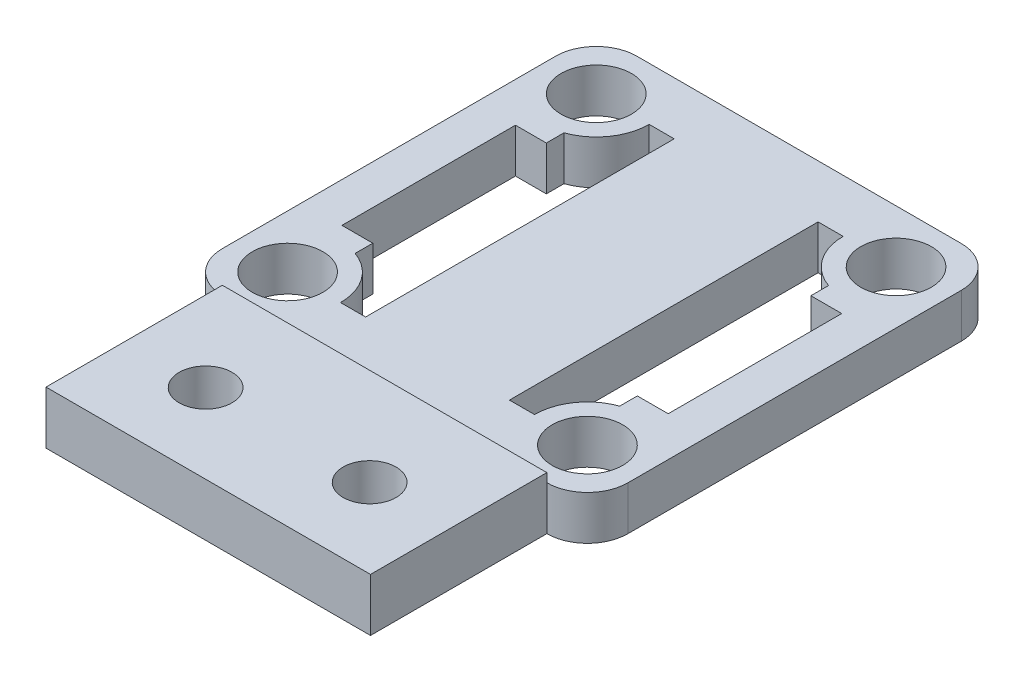
SolidWorks part; units mm, degrees
ref_plane "Front Plane" through (0, 0, 0) normal (0, 0, 1) x (1, 0, 0)
ref_plane "Top Plane" through (0, 0, 0) normal (0, 1, 0) x (1, 0, 0)
ref_plane "Right Plane" through (0, 0, 0) normal (1, 0, 0) x (0, 0, -1)
sketch "Sketch1" plane through (0, 0, 0) normal (0, 1, 0) x (1, 0, 0)
  line L1 (-12.6491, 14.6331) -> (5.7509, 14.6331)
  line L2 (-14.9491, 12.3331) -> (-14.9491, -6.5669)
  line L3 (-12.6491, -8.8669) -> (5.7509, -8.8669)
  line L4 (8.0509, 12.3331) -> (8.0509, -6.5669)
  line L5 (-14.9491, 14.6331) -> (8.0509, -8.8669) construction
  line L6 (-14.9491, -8.8669) -> (8.0509, 14.6331) construction
  arc A0 (8.0509, 12.3331) -> (5.7509, 14.6331) centre (5.7509, 12.3331) ccw
  arc A1 (-12.6491, -8.8669) -> (-14.9491, -6.5669) centre (-12.6491, -6.5669) cw
  arc A2 (5.7509, -8.8669) -> (8.0509, -6.5669) centre (5.7509, -6.5669) ccw
  arc A3 (-14.9491, 12.3331) -> (-12.6491, 14.6331) centre (-12.6491, 12.3331) cw
  point P0 (-3.4491, 2.8831)
  dimension "D3" = 2.3
  dimension "D4" = 2.3
  dimension "D1" = 23.5
  dimension "D2" = 23
extrude "Boss-Extrude1" add sketch "Sketch1" along normal blind 2
sketch "Sketch2" plane through (0, 2, 0) normal (0, 1, 0) x (1, 0, 0)
  line L8 (5.7509, 13.6331) -> (-12.6491, 13.6331)
  line L9 (-13.9491, 12.3331) -> (-13.9491, -6.5669)
  line L10 (-12.6491, -7.8669) -> (5.7509, -7.8669)
  line L11 (7.0509, -6.5669) -> (7.0509, 12.3331)
  line L12 (5.7509, 13.6331) -> (-12.6491, 13.6331)
  line L13 (-13.9491, 12.3331) -> (-13.9491, -6.5669)
  line L14 (-12.6491, -7.8669) -> (5.7509, -7.8669)
  line L15 (7.0509, -6.5669) -> (7.0509, 12.3331)
  arc A8 (7.0509, 12.3331) -> (5.7509, 13.6331) centre (5.7509, 12.3331) ccw
  arc A9 (-12.6491, 13.6331) -> (-13.9491, 12.3331) centre (-12.6491, 12.3331) ccw
  arc A10 (-13.9491, -6.5669) -> (-12.6491, -7.8669) centre (-12.6491, -6.5669) ccw
  arc A11 (5.7509, -7.8669) -> (7.0509, -6.5669) centre (5.7509, -6.5669) ccw
  arc A12 (7.0509, 12.3331) -> (5.7509, 13.6331) centre (5.7509, 12.3331) ccw
  arc A13 (-12.6491, 13.6331) -> (-13.9491, 12.3331) centre (-12.6491, 12.3331) ccw
  arc A14 (-13.9491, -6.5669) -> (-12.6491, -7.8669) centre (-12.6491, -6.5669) ccw
  arc A15 (5.7509, -7.8669) -> (7.0509, -6.5669) centre (5.7509, -6.5669) ccw
  dimension "D1" = 1
extrude "Cut-Extrude2" cut sketch "Sketch2" against normal blind 1
sketch "Sketch5" plane through (0, 1, 0) normal (0, 1, 0) x (1, 0, 0)
  line L0 (-3.4491, 13.6331) -> (-3.4491, -7.8669) construction
  line L1 (5.7509, 13.6331) -> (-12.6491, 13.6331) construction
  line L2 (-12.6491, -7.8669) -> (5.7509, -7.8669) construction
  line L3 (7.0509, 2.8831) -> (-13.9491, 2.8831) construction
  line L4 (7.0509, -6.5669) -> (7.0509, 12.3331) construction
  line L5 (-13.9491, 12.3331) -> (-13.9491, -6.5669) construction
  circle A0 centre (5.0509, 11.6331) radius 2
  circle A1 centre (5.0509, -5.8669) radius 2
  circle A2 centre (-11.9491, -5.8669) radius 2
  circle A3 centre (-11.9491, 11.6331) radius 2
  dimension "D1" = 4
extrude "Cut-Extrude3" cut sketch "Sketch5" against normal through all
sketch "Sketch6" plane through (0, 1, 0) normal (0, 1, 0) x (1, 0, 0)
  line L0 (-14.9491, 12.3331) -> (-14.9491, -6.5669) construction
  line L1 (8.0509, -6.5669) -> (8.0509, 12.3331) construction
  line L14 (4.0509, -5.8669) -> (4.0509, 11.6331)
  line L15 (4.0509, -3.0385) -> (4.0509, 8.8047)
  line L16 (2.0509, 11.6331) -> (2.0509, -5.8669)
  line L17 (-10.9491, 12.3331) -> (-10.9491, -6.5669)
  line L18 (-10.9491, 8.8047) -> (-10.9491, -3.0385)
  line L19 (-8.9491, 11.6331) -> (-8.9491, -5.8669)
  arc A5 (-11.9491, -8.8669) -> (-14.9491, -5.8669) centre (-11.9491, -5.8669) ccw
  arc A6 (-8.9491, -5.8669) -> (-10.9491, -3.0385) centre (-11.9491, -5.8669) ccw
  arc A20 (5.0509, 14.6331) -> (8.0509, 11.6331) centre (5.0509, 11.6331) ccw
  arc A21 (2.0509, 11.6331) -> (4.0509, 8.8047) centre (5.0509, 11.6331) ccw
  arc A23 (-14.9491, 11.6331) -> (-11.9491, 14.6331) centre (-11.9491, 11.6331) ccw
  arc A24 (-10.9491, 8.8047) -> (-8.9491, 11.6331) centre (-11.9491, 11.6331) ccw
  arc A26 (8.0509, -5.8669) -> (5.0509, -8.8669) centre (5.0509, -5.8669) ccw
  arc A27 (4.0509, -3.0385) -> (2.0509, -5.8669) centre (5.0509, -5.8669) ccw
  dimension "D1" = 23
  dimension "D2" = 1
  dimension "D3" = 1
  dimension "D4" = 1
  dimension "D5" = 1
  dimension "D6" = 3
  dimension "D7" = 3
extrude "Cut-Extrude4" cut sketch "Sketch6" against normal through all
sketch "Sketch7" plane through (0, 0, 8.8669) normal (0, 0, 1) x (1, 0, 0)
  line L0 (-14.9491, 2) -> (-14.9491, 0) construction
  line L1 (8.0509, 2) -> (8.0509, 0) construction
  line L2 (-12.6491, 2) -> (-12.6491, 0) construction
  line L3 (-12.6491, 1) -> (5.7509, 1)
  line L4 (5.7509, 2) -> (5.7509, 0) construction
  line L5 (5.7509, 1) -> (5.7509, 0)
  line L6 (5.7509, 0) -> (-12.6491, 0)
  line L7 (-12.6491, 0) -> (-12.6491, 1)
  line L8 (-12.6491, 2) -> (5.7509, 2) construction
  dimension "D1" = 23
extrude "Boss-Extrude2" add sketch "Sketch7" along normal blind 10
sketch "Sketch9" plane through (0, 2, 0) normal (0, 1, 0) x (1, 0, 0)
  line L8 (5.7509, 13.8331) -> (-12.6491, 13.8331)
  line L9 (-14.1491, 12.3331) -> (-14.1491, -6.5669)
  line L10 (-12.6491, -8.0669) -> (5.7509, -8.0669)
  line L11 (7.2509, -6.5669) -> (7.2509, 12.3331)
  line L12 (5.7509, 13.8331) -> (-12.6491, 13.8331)
  line L13 (-14.1491, 12.3331) -> (-14.1491, -6.5669)
  line L14 (-12.6491, -8.0669) -> (5.7509, -8.0669)
  line L15 (7.2509, -6.5669) -> (7.2509, 12.3331)
  arc A8 (7.2509, 12.3331) -> (5.7509, 13.8331) centre (5.7509, 12.3331) ccw
  arc A9 (-12.6491, 13.8331) -> (-14.1491, 12.3331) centre (-12.6491, 12.3331) ccw
  arc A10 (-14.1491, -6.5669) -> (-12.6491, -8.0669) centre (-12.6491, -6.5669) ccw
  arc A11 (5.7509, -8.0669) -> (7.2509, -6.5669) centre (5.7509, -6.5669) ccw
  arc A12 (7.2509, 12.3331) -> (5.7509, 13.8331) centre (5.7509, 12.3331) ccw
  arc A13 (-12.6491, 13.8331) -> (-14.1491, 12.3331) centre (-12.6491, 12.3331) ccw
  arc A14 (-14.1491, -6.5669) -> (-12.6491, -8.0669) centre (-12.6491, -6.5669) ccw
  arc A15 (5.7509, -8.0669) -> (7.2509, -6.5669) centre (5.7509, -6.5669) ccw
  dimension "D1" = 0.8
extrude "Cut-Extrude6" cut sketch "Sketch9" against normal blind 1
sketch "Sketch11" plane through (0, 1, 0) normal (0, 1, 0) x (1, 0, 0)
  line L0 (-8.9491, 11.6331) -> (-7.528, 11.6331)
  line L1 (-7.528, 11.6331) -> (-7.528, -5.8669)
  line L2 (-7.528, -5.8669) -> (-8.9491, -5.8669)
  line L3 (-8.9491, -5.8669) -> (-8.9491, 11.6331)
  line L4 (-3.4491, 13.8331) -> (-3.4491, -8.0669) construction
  line L5 (5.7509, 13.8331) -> (-12.6491, 13.8331) construction
  line L6 (-12.6491, -8.0669) -> (5.7509, -8.0669) construction
  line L7 (0.6299, -5.8669) -> (2.0509, -5.8669)
  line L8 (0.6299, 11.6331) -> (0.6299, -5.8669)
  line L9 (2.0509, 11.6331) -> (0.6299, 11.6331)
  line L10 (2.0509, -5.8669) -> (2.0509, 11.6331)
  line L11 (-10.9491, 8.8047) -> (-10.9491, -3.0385) construction
  line L12 (-12.6991, 7.8031) -> (-10.9491, 7.8031)
  line L13 (-12.6991, 7.8031) -> (-12.6991, -2.0369)
  line L14 (-12.6991, -2.0369) -> (-10.9491, -2.0369)
  line L15 (-10.9491, 7.8031) -> (-10.9491, -2.0369)
  line L16 (5.8009, -2.0369) -> (4.0509, -2.0369)
  line L17 (4.0509, 7.8031) -> (4.0509, -2.0369)
  line L18 (5.8009, 7.8031) -> (4.0509, 7.8031)
  line L19 (5.8009, 7.8031) -> (5.8009, -2.0369)
  point P22 (-10.9491, 2.8831)
  point P23 (-10.9491, 2.8831)
  dimension "D1" = 9.84
  dimension "D2" = 1.75
extrude "Cut-Extrude7" cut sketch "Sketch11" against normal through all
sketch "Sketch12" plane through (0, 0, 0) normal (0, -1, 0) x (1, 0, 0)
  line L6 (8.0509, -12.3331) -> (8.0509, 6.5669)
  line L7 (5.7509, 8.8669) -> (5.7509, 18.8669)
  line L8 (5.7509, 18.8669) -> (-12.6491, 18.8669)
  line L9 (-12.6491, 18.8669) -> (-12.6491, 8.8669)
  line L10 (-14.9491, 6.5669) -> (-14.9491, -12.3331)
  line L11 (-12.6491, -14.6331) -> (5.7509, -14.6331)
  line L12 (8.0509, -12.3331) -> (8.0509, 6.5669)
  line L13 (5.7509, 8.8669) -> (5.7509, 18.8669)
  line L14 (5.7509, 18.8669) -> (-12.6491, 18.8669)
  line L15 (-12.6491, 18.8669) -> (-12.6491, 8.8669)
  line L16 (-14.9491, 6.5669) -> (-14.9491, -12.3331)
  line L17 (-12.6491, -14.6331) -> (5.7509, -14.6331)
  arc A4 (5.7509, -14.6331) -> (8.0509, -12.3331) centre (5.7509, -12.3331) ccw
  arc A5 (8.0509, 6.5669) -> (5.7509, 8.8669) centre (5.7509, 6.5669) ccw
  arc A6 (-12.6491, 8.8669) -> (-14.9491, 6.5669) centre (-12.6491, 6.5669) ccw
  arc A7 (-14.9491, -12.3331) -> (-12.6491, -14.6331) centre (-12.6491, -12.3331) ccw
  arc A8 (5.7509, -14.6331) -> (8.0509, -12.3331) centre (5.7509, -12.3331) ccw
  arc A9 (8.0509, 6.5669) -> (5.7509, 8.8669) centre (5.7509, 6.5669) ccw
  arc A10 (-12.6491, 8.8669) -> (-14.9491, 6.5669) centre (-12.6491, 6.5669) ccw
  arc A11 (-14.9491, -12.3331) -> (-12.6491, -14.6331) centre (-12.6491, -12.3331) ccw
  dimension "D1" = 0
extrude "Boss-Extrude3" add sketch "Sketch12" along normal blind 2
sketch "Sketch13" plane through (0, 0, 0) normal (0, 1, 0) x (1, 0, 0)
  line L8 (-12.6991, 7.8031) -> (-12.6991, -2.0369)
  line L9 (-12.6991, -2.0369) -> (-10.9491, -2.0369)
  line L10 (-10.9491, -2.0369) -> (-10.9491, -3.0385)
  line L11 (-8.9491, -5.8669) -> (-7.528, -5.8669)
  line L12 (-7.528, -5.8669) -> (-7.528, 11.6331)
  line L13 (-7.528, 11.6331) -> (-8.9491, 11.6331)
  line L14 (-10.9491, 8.8047) -> (-10.9491, 7.8031)
  line L15 (-10.9491, 7.8031) -> (-12.6991, 7.8031)
  line L16 (-12.6991, 7.8031) -> (-12.6991, -2.0369)
  line L17 (-12.6991, -2.0369) -> (-10.9491, -2.0369)
  line L18 (-10.9491, -2.0369) -> (-10.9491, -3.0385)
  line L19 (-8.9491, -5.8669) -> (-7.528, -5.8669)
  line L20 (-7.528, -5.8669) -> (-7.528, 11.6331)
  line L21 (-7.528, 11.6331) -> (-8.9491, 11.6331)
  line L22 (-10.9491, 8.8047) -> (-10.9491, 7.8031)
  line L23 (-10.9491, 7.8031) -> (-12.6991, 7.8031)
  arc A2 (-8.9491, -5.8669) -> (-10.9491, -3.0385) centre (-11.9491, -5.8669) ccw
  arc A3 (-10.9491, 8.8047) -> (-8.9491, 11.6331) centre (-11.9491, 11.6331) ccw
  arc A4 (-8.9491, -5.8669) -> (-10.9491, -3.0385) centre (-11.9491, -5.8669) ccw
  arc A5 (-10.9491, 8.8047) -> (-8.9491, 11.6331) centre (-11.9491, 11.6331) ccw
  dimension "D1" = 0
extrude "Cut-Extrude8" cut sketch "Sketch13" against normal through all both and the other way through all
sketch "Sketch14" plane through (0, 0, 0) normal (0, 1, 0) x (1, 0, 0)
  line L8 (0.6299, -5.8669) -> (2.0509, -5.8669)
  line L9 (4.0509, -3.0385) -> (4.0509, -2.0369)
  line L10 (4.0509, -2.0369) -> (5.8009, -2.0369)
  line L11 (5.8009, -2.0369) -> (5.8009, 7.8031)
  line L12 (5.8009, 7.8031) -> (4.0509, 7.8031)
  line L13 (4.0509, 7.8031) -> (4.0509, 8.8047)
  line L14 (2.0509, 11.6331) -> (0.6299, 11.6331)
  line L15 (0.6299, 11.6331) -> (0.6299, -5.8669)
  line L16 (0.6299, -5.8669) -> (2.0509, -5.8669)
  line L17 (4.0509, -3.0385) -> (4.0509, -2.0369)
  line L18 (4.0509, -2.0369) -> (5.8009, -2.0369)
  line L19 (5.8009, -2.0369) -> (5.8009, 7.8031)
  line L20 (5.8009, 7.8031) -> (4.0509, 7.8031)
  line L21 (4.0509, 7.8031) -> (4.0509, 8.8047)
  line L22 (2.0509, 11.6331) -> (0.6299, 11.6331)
  line L23 (0.6299, 11.6331) -> (0.6299, -5.8669)
  arc A2 (4.0509, -3.0385) -> (2.0509, -5.8669) centre (5.0509, -5.8669) ccw
  arc A3 (2.0509, 11.6331) -> (4.0509, 8.8047) centre (5.0509, 11.6331) ccw
  arc A4 (4.0509, -3.0385) -> (2.0509, -5.8669) centre (5.0509, -5.8669) ccw
  arc A5 (2.0509, 11.6331) -> (4.0509, 8.8047) centre (5.0509, 11.6331) ccw
  dimension "D1" = 0
extrude "Cut-Extrude9" cut sketch "Sketch14" against normal through all both and the other way through all
sketch "Sketch17" plane through (0, 0, 0) normal (0, 1, 0) x (1, 0, 0)
  circle A0 centre (-11.9491, -5.8669) radius 2 construction
  circle A1 centre (5.0509, -5.8669) radius 2 construction
  circle A2 centre (-11.9491, 11.6331) radius 2 construction
  circle A3 centre (5.0509, 11.6331) radius 2 construction
  circle A4 centre (-11.9491, -5.8669) radius 2
  circle A5 centre (5.0509, -5.8669) radius 2
  circle A6 centre (-11.9491, 11.6331) radius 2
  circle A7 centre (5.0509, 11.6331) radius 2
extrude "Cut-Extrude12" cut sketch "Sketch17" against normal through all both and the other way through all
sketch "Sketch18" plane through (0, 1, 0) normal (0, 1, 0) x (1, 0, 0)
  line L4 (5.7509, 13.8331) -> (-12.6491, 13.8331)
  line L5 (-14.1491, 12.3331) -> (-14.1491, -6.5669)
  line L6 (-12.6491, -8.0669) -> (5.7509, -8.0669)
  line L7 (7.2509, -6.5669) -> (7.2509, 12.3331)
  line L8 (5.7509, 13.8331) -> (-12.6491, 13.8331)
  line L9 (-14.1491, 12.3331) -> (-14.1491, -6.5669)
  line L10 (-12.6491, -8.0669) -> (5.7509, -8.0669)
  line L11 (7.2509, -6.5669) -> (7.2509, 12.3331)
  arc A4 (7.2509, 12.3331) -> (5.7509, 13.8331) centre (5.7509, 12.3331) ccw
  arc A5 (-12.6491, 13.8331) -> (-14.1491, 12.3331) centre (-12.6491, 12.3331) ccw
  arc A6 (-14.1491, -6.5669) -> (-12.6491, -8.0669) centre (-12.6491, -6.5669) ccw
  arc A7 (5.7509, -8.0669) -> (7.2509, -6.5669) centre (5.7509, -6.5669) ccw
  arc A8 (7.2509, 12.3331) -> (5.7509, 13.8331) centre (5.7509, 12.3331) ccw
  arc A9 (-12.6491, 13.8331) -> (-14.1491, 12.3331) centre (-12.6491, 12.3331) ccw
  arc A10 (-14.1491, -6.5669) -> (-12.6491, -8.0669) centre (-12.6491, -6.5669) ccw
  arc A11 (5.7509, -8.0669) -> (7.2509, -6.5669) centre (5.7509, -6.5669) ccw
  dimension "D1" = 0
extrude "Boss-Extrude4" add sketch "Sketch18" along normal up to surface (1 mm away) up to face at (-3.4491, 2, -2.8831)
sketch "Sketch19" plane through (0, 1, 0) normal (0, -1, 0) x (1, 0, 0)
  line L8 (-10.9491, 3.0385) -> (-10.9491, 2.0369)
  line L9 (-10.9491, 2.0369) -> (-12.6991, 2.0369)
  line L10 (-12.6991, 2.0369) -> (-12.6991, -7.8031)
  line L11 (-12.6991, -7.8031) -> (-10.9491, -7.8031)
  line L12 (-10.9491, -7.8031) -> (-10.9491, -8.8047)
  line L13 (-8.9491, -11.6331) -> (-7.528, -11.6331)
  line L14 (-7.528, -11.6331) -> (-7.528, 5.8669)
  line L15 (-7.528, 5.8669) -> (-8.9491, 5.8669)
  line L16 (-10.9491, 3.0385) -> (-10.9491, 2.0369)
  line L17 (-10.9491, 2.0369) -> (-12.6991, 2.0369)
  line L18 (-12.6991, 2.0369) -> (-12.6991, -7.8031)
  line L19 (-12.6991, -7.8031) -> (-10.9491, -7.8031)
  line L20 (-10.9491, -7.8031) -> (-10.9491, -8.8047)
  line L21 (-8.9491, -11.6331) -> (-7.528, -11.6331)
  line L22 (-7.528, -11.6331) -> (-7.528, 5.8669)
  line L23 (-7.528, 5.8669) -> (-8.9491, 5.8669)
  line L24 (4.0509, 2.0369) -> (4.0509, 3.0385)
  line L25 (2.0509, 5.8669) -> (0.6299, 5.8669)
  line L26 (0.6299, 5.8669) -> (0.6299, -11.6331)
  line L27 (0.6299, -11.6331) -> (2.0509, -11.6331)
  line L28 (4.0509, -8.8047) -> (4.0509, -7.8031)
  line L29 (4.0509, -7.8031) -> (5.8009, -7.8031)
  line L30 (5.8009, -7.8031) -> (5.8009, 2.0369)
  line L31 (5.8009, 2.0369) -> (4.0509, 2.0369)
  line L32 (4.0509, 2.0369) -> (4.0509, 3.0385)
  line L33 (2.0509, 5.8669) -> (0.6299, 5.8669)
  line L34 (0.6299, 5.8669) -> (0.6299, -11.6331)
  line L35 (0.6299, -11.6331) -> (2.0509, -11.6331)
  line L36 (4.0509, -8.8047) -> (4.0509, -7.8031)
  line L37 (4.0509, -7.8031) -> (5.8009, -7.8031)
  line L38 (5.8009, -7.8031) -> (5.8009, 2.0369)
  line L39 (5.8009, 2.0369) -> (4.0509, 2.0369)
  circle A0 centre (5.0509, -11.6331) radius 2 construction
  circle A1 centre (-11.9491, -11.6331) radius 2 construction
  arc A2 (-8.9491, -11.6331) -> (-10.9491, -8.8047) centre (-11.9491, -11.6331) ccw
  arc A3 (-10.9491, 3.0385) -> (-8.9491, 5.8669) centre (-11.9491, 5.8669) ccw
  arc A4 (-8.9491, -11.6331) -> (-10.9491, -8.8047) centre (-11.9491, -11.6331) ccw
  arc A5 (-10.9491, 3.0385) -> (-8.9491, 5.8669) centre (-11.9491, 5.8669) ccw
  arc A6 (2.0509, 5.8669) -> (4.0509, 3.0385) centre (5.0509, 5.8669) ccw
  arc A7 (4.0509, -8.8047) -> (2.0509, -11.6331) centre (5.0509, -11.6331) ccw
  arc A8 (2.0509, 5.8669) -> (4.0509, 3.0385) centre (5.0509, 5.8669) ccw
  arc A9 (4.0509, -8.8047) -> (2.0509, -11.6331) centre (5.0509, -11.6331) ccw
  circle A10 centre (-11.9491, 5.8669) radius 2 construction
  circle A11 centre (5.0509, 5.8669) radius 2 construction
  circle A12 centre (5.0509, -11.6331) radius 2
  circle A13 centre (-11.9491, -11.6331) radius 2
  circle A14 centre (-11.9491, 5.8669) radius 2
  circle A15 centre (5.0509, 5.8669) radius 2
  dimension "D1" = 0
  dimension "D2" = 0
extrude "Cut-Extrude13" cut sketch "Sketch19" against normal through all both and the other way through all
sketch "Sketch20" plane through (0, 2, 0) normal (0, 1, 0) x (1, 0, 0)
  line L4 (5.7509, 14.6331) -> (-12.6491, 14.6331)
  line L5 (-14.9491, 12.3331) -> (-14.9491, -6.5669)
  line L6 (-12.6491, -8.8669) -> (5.7509, -8.8669)
  line L7 (8.0509, -6.5669) -> (8.0509, 12.3331)
  line L8 (5.7509, 14.6331) -> (-12.6491, 14.6331)
  line L9 (-14.9491, 12.3331) -> (-14.9491, -6.5669)
  line L10 (-12.6491, -8.8669) -> (5.7509, -8.8669)
  line L11 (8.0509, -6.5669) -> (8.0509, 12.3331)
  arc A4 (8.0509, 12.3331) -> (5.7509, 14.6331) centre (5.7509, 12.3331) ccw
  arc A5 (-12.6491, 14.6331) -> (-14.9491, 12.3331) centre (-12.6491, 12.3331) ccw
  arc A6 (-14.9491, -6.5669) -> (-12.6491, -8.8669) centre (-12.6491, -6.5669) ccw
  arc A7 (5.7509, -8.8669) -> (8.0509, -6.5669) centre (5.7509, -6.5669) ccw
  arc A8 (8.0509, 12.3331) -> (5.7509, 14.6331) centre (5.7509, 12.3331) ccw
  arc A9 (-12.6491, 14.6331) -> (-14.9491, 12.3331) centre (-12.6491, 12.3331) ccw
  arc A10 (-14.9491, -6.5669) -> (-12.6491, -8.8669) centre (-12.6491, -6.5669) ccw
  arc A11 (5.7509, -8.8669) -> (8.0509, -6.5669) centre (5.7509, -6.5669) ccw
  dimension "D1" = 0
extrude "Cut-Extrude14" cut sketch "Sketch20" against normal blind 1.5
sketch "Sketch22" plane through (0, 1, 0) normal (0, 1, 0) x (1, 0, 0)
  line L0 (-12.6491, -8.8669) -> (5.7509, -8.8669) construction
  line L1 (5.7509, -18.8669) -> (5.7509, -8.8669) construction
  line L2 (-3.4491, -8.8669) -> (-3.4491, -18.8669) construction
  line L3 (5.7509, -8.8669) -> (-12.6491, -8.8669) construction
  line L4 (5.7509, -18.8669) -> (-12.6491, -18.8669) construction
  line L5 (-12.6491, -18.8669) -> (-12.6491, -8.8669) construction
  circle A0 centre (-8.0991, -14.3669) radius 1.5
  circle A1 centre (1.2009, -14.3669) radius 1.5
  point P4 (0, 0)
  point P5 (0, 0)
  dimension "D1" = 3
  dimension "D2" = 5.5
  dimension "D3" = 4.55
  dimension "D4" = 4.55
extrude "Cut-Extrude17" cut sketch "Sketch22" against normal blind 10
